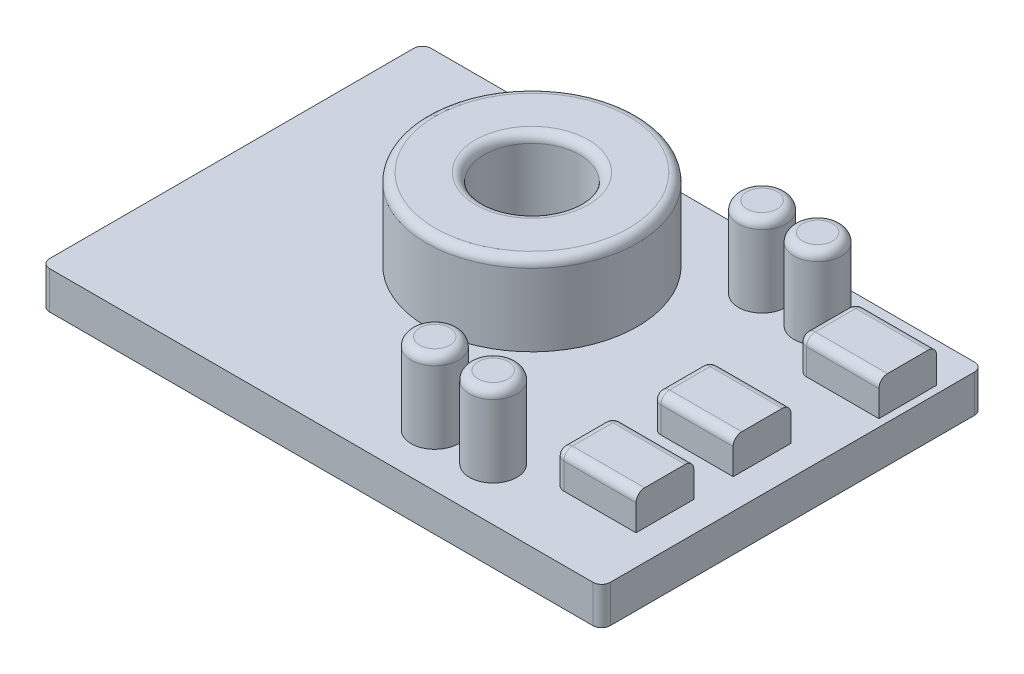
SolidWorks part; units mm, degrees
ref_plane "前视基准面" through (0, 0, 0) normal (0, 0, 1) x (1, 0, 0)
ref_plane "上视基准面" through (0, 0, 0) normal (0, 1, 0) x (1, 0, 0)
ref_plane "右视基准面" through (0, 0, 0) normal (1, 0, 0) x (0, 0, -1)
sketch "Sketch1" plane through (0, 0, 0) normal (0, 1, 0) x (1, 0, 0)
  line L1 (-48.5, -33) -> (48.5, -33)
  line L2 (-48.5, -33) -> (-48.5, 33)
  line L3 (-48.5, 33) -> (48.5, 33)
  line L4 (48.5, -33) -> (48.5, 33)
  line L5 (-48.5, -33) -> (48.5, 33) construction
  line L6 (-48.5, 33) -> (48.5, -33) construction
  point P0 (0, 0)
  dimension "D1" = 97
  dimension "D2" = 66
extrude "Extrude1" add sketch "Sketch1" along normal blind 6.5
sketch "Sketch2" plane through (0, 6.5, 0) normal (0, 1, 0) x (1, 0, 0)
  circle A0 centre (-5.7022, 9.1535) radius 18.25
  circle A1 centre (-5.7022, 9.1535) radius 8.25
  circle A2 centre (18.407, 24.8595) radius 4.1
  circle A3 centre (28.0107, 24.8595) radius 4.1
  circle A4 centre (10.504, -23.8591) radius 4.1
  circle A5 centre (20.6078, -23.8591) radius 4.1
  point P11 (20.3077, -25.0595)
  point P12 (10.1038, -25.0595)
  point P13 (20.6078, -23.8591)
  point P14 (10.504, -23.8591)
  point P15 (18.407, 24.8595)
  point P16 (28.0107, 24.8595)
  point P17 (-5.7022, 9.1535)
  dimension "D1" = 8.2
  dimension "D2" = 36.5
  dimension "D3" = 16.5
extrude "Extrude2" add sketch "Sketch2" along normal blind 14
sketch "Sketch3" plane through (0, 6.5, 0) normal (0, 1, 0) x (1, 0, 0)
  line L1 (33.2126, 16.2562) -> (47.2126, 16.2562)
  line L2 (33.2126, 16.2562) -> (33.2126, 26.2562)
  line L3 (33.2126, 26.2562) -> (47.2126, 26.2562)
  line L4 (47.2126, 16.2562) -> (47.2126, 26.2562)
  line L5 (29.3112, -5.0519) -> (43.3112, -5.0519)
  line L6 (29.3112, -5.0519) -> (29.3112, 4.9481)
  line L7 (29.3112, 4.9481) -> (43.3112, 4.9481)
  line L8 (43.3112, -5.0519) -> (43.3112, 4.9481)
  line L9 (29.3112, -21.8583) -> (43.3112, -21.8583)
  line L10 (29.3112, -21.8583) -> (29.3112, -11.8583)
  line L11 (29.3112, -11.8583) -> (43.3112, -11.8583)
  line L12 (43.3112, -21.8583) -> (43.3112, -11.8583)
  dimension "D1" = 10
  dimension "D2" = 14
extrude "Extrude3" add sketch "Sketch3" along normal blind 6
fillet "Fillet1" radius 1.5 4 edges at (48.5, 3.25, -33) (48.5, 3.25, 33) (-48.5, 3.25, -33) (-48.5, 3.25, 33)
fillet "Fillet2" radius 1.5 12 edges at (36.3112, 12.5, 21.8583) (36.3112, 12.5, 11.8583) (36.3112, 12.5, 5.0519) (36.3112, 12.5, -4.9481) (40.2126, 12.5, -26.2562) (40.2126, 12.5, -16.2562) (18.407, 20.5, -20.7595) (28.0107, 20.5, -20.7595) (10.504, 20.5, 27.9591) (20.6078, 20.5, 27.9591) (-5.7022, 20.5, -0.9035) (-5.7022, 20.5, 9.0965)
fillet "Fillet3" radius 1.5 15 edges at (29.3112, 8.75, 11.8583) (29.3112, 12.0607, 12.2977) (29.3112, 8.75, 21.8583) (29.3112, 12.0607, 21.419) (29.3112, 8.75, -4.9481) (29.3112, 12.0607, -4.5087) (29.3112, 8.75, 5.0519) (29.3112, 12.0607, 4.6126) (33.2126, 8.75, -26.2562) (33.2126, 12.0607, -25.8168) (33.2126, 8.75, -16.2562) (33.2126, 12.0607, -16.6955) (29.3112, 12.5, 16.8583) (29.3112, 12.5, 0.0519) (33.2126, 12.5, -21.2562)
